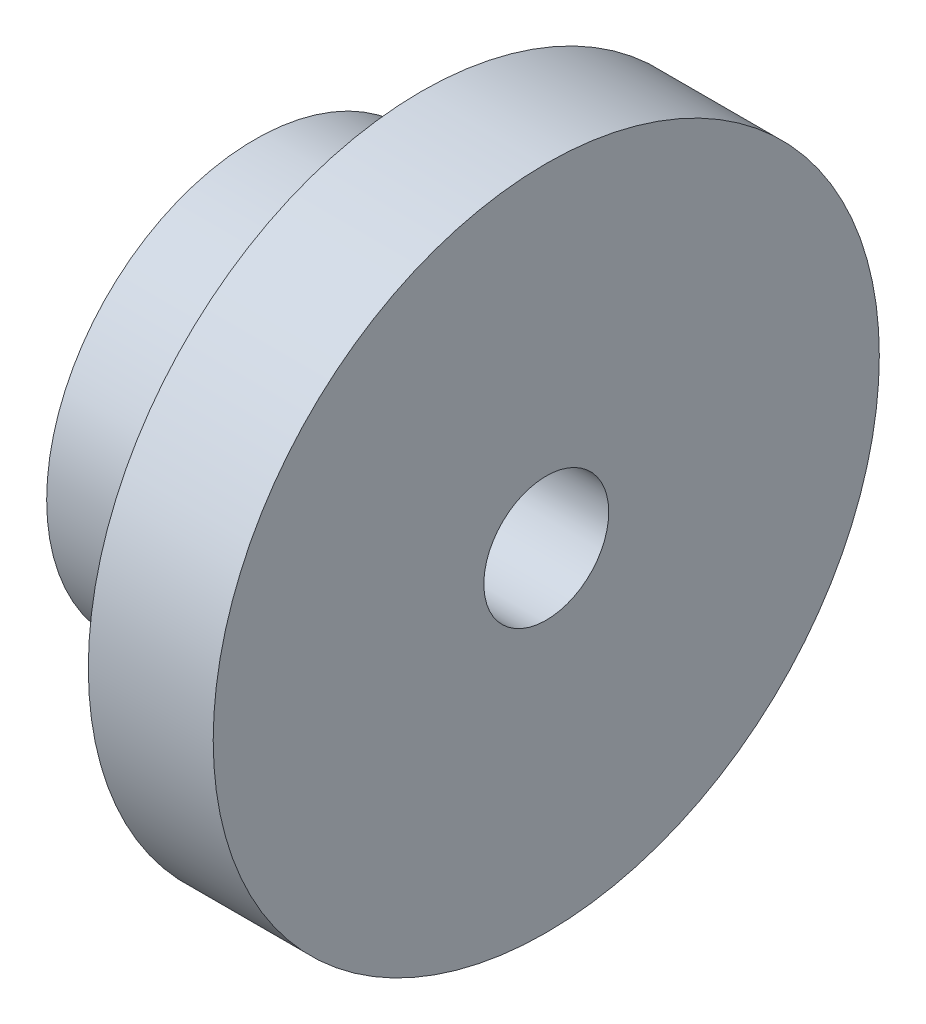
SolidWorks part; units mm, degrees
material "Nylon 101"
ref_plane "Front Plane" through (0, 0, 0) normal (0, 0, 1) x (1, 0, 0)
ref_plane "Top Plane" through (0, 0, 0) normal (0, 1, 0) x (1, 0, 0)
ref_plane "Right Plane" through (0, 0, 0) normal (1, 0, 0) x (0, 0, -1)
sketch "Sketch1" plane through (0, 0, 0) normal (1, 0, 0) x (0, 0, -1)
  circle A0 centre (0, 0) radius 12.7
  dimension "D1" = 25.4
extrude "Boss-Extrude1" add sketch "Sketch1" along normal blind 4.7625
sketch "Sketch2" plane through (0, 0, 0) normal (-1, 0, 0) x (0, 0, 1)
  circle A0 centre (0, 0) radius 7.9375
  dimension "D1" = 15.875
extrude "Boss-Extrude2" add sketch "Sketch2" along normal blind 6.35
hole_wizard "#4 Clearance Hole1" positions "Sketch4" profile "Sketch5" hole size "#4" standard "ANSI Inch" end condition through all
sketch "Sketch4" plane through (4.7625, 0, 0) normal (1, 0, 0) x (0, 0, -1)
  point P0 (0, 0)
sketch "Sketch5" plane through (4.7625, 0, 0) normal (0, 1, 0) x (0, 0, -1)
  line L0 (0, 0) -> (0, 11.1125)
  line L1 (0, 11.1125) -> (2.3812, 11.1125)
  line L2 (2.3812, 11.1125) -> (2.3812, 0)
  line L5 (2.3812, 0) -> (0, 0)
  line L11 (0, -6.35) -> (0, 107.95) construction
  dimension "Thru Hole Dia." = 4.7625
  dimension "Thru Hole Depth" = 11.1125
